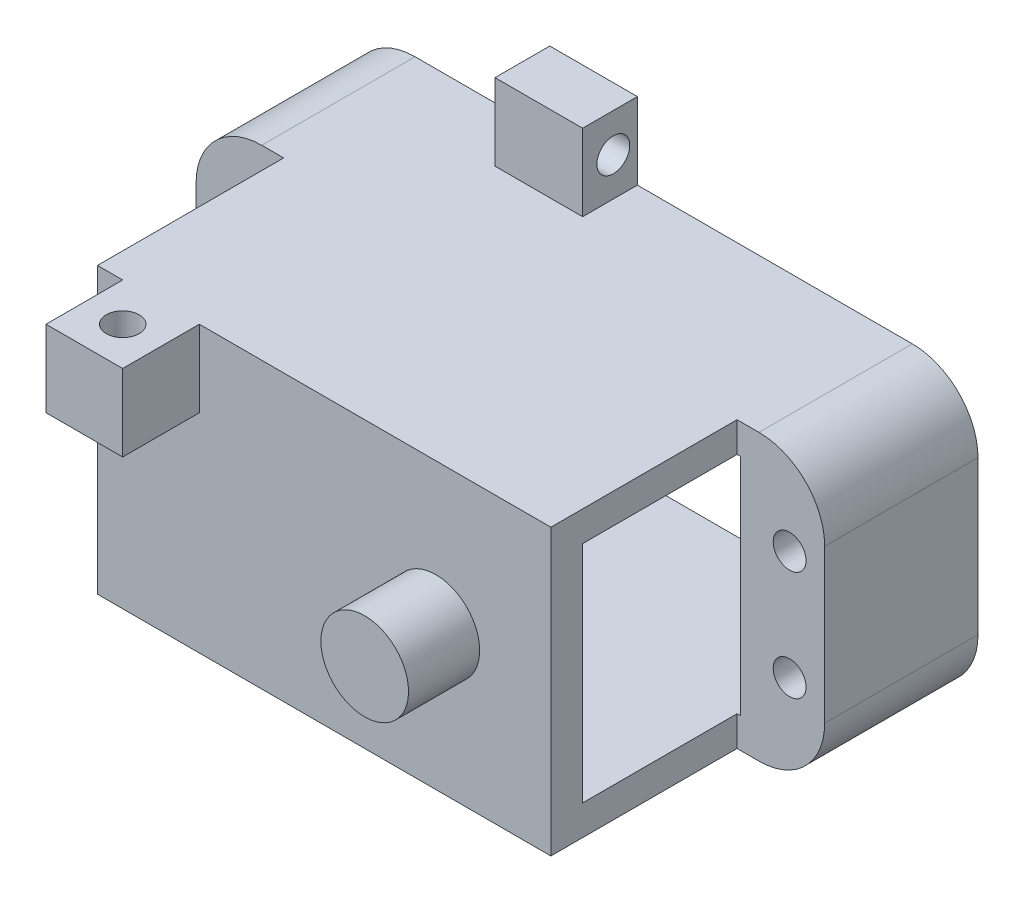
SolidWorks part; units mm, degrees
ref_plane "Спереди" through (0, 0, 0) normal (0, 0, 1) x (1, 0, 0)
ref_plane "Сверху" through (0, 0, 0) normal (0, 1, 0) x (1, 0, 0)
ref_plane "Справа" through (0, 0, 0) normal (1, 0, 0) x (0, 0, -1)
sketch "Эскиз1" plane through (0, 0, 0) normal (0, 0, 1) x (1, 0, 0)
  line L1 (-28.7, -13) -> (28.7, -13)
  line L2 (-28.7, -13) -> (-28.7, 13)
  line L3 (-28.7, 13) -> (28.7, 13)
  line L4 (28.7, -13) -> (28.7, 13)
  line L5 (-28.7, -13) -> (28.7, 13) construction
  line L6 (-28.7, 13) -> (28.7, -13) construction
  point P0 (0, 0)
  dimension "D1" = 26
  dimension "D2" = 57.4
extrude "Бобышка-Вытянуть1" add sketch "Эскиз1" along normal blind 31
sketch "Эскиз3" plane through (0, 0, 0) normal (0, 0, 1) x (1, 0, 0)
  line L1 (-21, -10.25) -> (21, -10.25)
  line L2 (-21, -10.25) -> (-21, 10.25)
  line L3 (-21, 10.25) -> (21, 10.25)
  line L4 (21, -10.25) -> (21, 10.25)
  line L5 (-21, -10.25) -> (21, 10.25) construction
  line L6 (-21, 10.25) -> (21, -10.25) construction
  point P0 (0, 0)
  dimension "D1" = 42
  dimension "D2" = 20.5
extrude "Вырез-Вытянуть1" cut sketch "Эскиз3" along normal blind 28.1
sketch "Эскиз5" plane through (0, 0, 0) normal (0, 0, 1) x (1, 0, 0)
  line L0 (-28.7, 13) -> (-18.4, 13)
  line L1 (28.7, 13) -> (-28.7, 13) construction
  line L3 (-18.4, 13) -> (-11.4, 13)
  line L4 (-18.4, 13) -> (-18.4, 6)
  line L5 (-18.4, 6) -> (-11.4, 6)
  line L6 (-11.4, 13) -> (-11.4, 6)
  dimension "D1" = 10.3
  dimension "D2" = 7
  dimension "D3" = 7
extrude "Бобышка-Вытянуть2" add sketch "Эскиз5" along normal blind 7 from surface at 31 contours L3 L6 L5 L4 starting at face at (0, 0, 31)
sketch "Эскиз6" plane through (0, 0, 0) normal (0, 0, 1) x (1, 0, 0)
  line L0 (-28.7, 13) -> (-10.4, 13)
  line L1 (28.7, 13) -> (-11.4, 13) construction
  line L3 (-10.4, 13) -> (-2.4, 13)
  line L4 (-10.4, 13) -> (-10.4, 20)
  line L5 (-10.4, 20) -> (-2.4, 20)
  line L6 (-2.4, 13) -> (-2.4, 20)
  dimension "D1" = 18.3
  dimension "D2" = 8
  dimension "D3" = 7
extrude "Бобышка-Вытянуть3" add sketch "Эскиз6" along normal blind 5 contours L3 L6 L5 L4
sketch "Эскиз7" plane through (0, 13, 0) normal (0, 1, 0) x (1, 0, 0)
  line L0 (-18.4, -31) -> (-14.9, -31)
  line L1 (-14.9, -31) -> (-14.9, -34.5)
  circle A0 centre (-14.9, -34.5) radius 1.5
  dimension "D3" = 3
  dimension "D1" = 3.5
  dimension "D2" = 3.5
extrude "Вырез-Вытянуть2" cut sketch "Эскиз7" against normal up to surface (7 mm away) contours A0 up to face at (-14.9, 6, 34.5)
sketch "Эскиз8" plane through (-10.4, 0, 0) normal (-1, 0, 0) x (0, 0, 1)
  line L0 (0, 20) -> (0, 16.5)
  line L1 (0, 13) -> (0, 20) construction
  line L2 (0, 16.5) -> (2.2, 16.5)
  circle A0 centre (2.2, 16.5) radius 1.5
  dimension "D2" = 3
  dimension "D1" = 2.2
extrude "Вырез-Вытянуть3" cut sketch "Эскиз8" against normal up to surface (8 mm away) contours A0 up to face at (-2.4, 16.5, 2.5)
sketch "Эскиз10" plane through (-28.7, 0, 0) normal (-1, 0, 0) x (0, 0, 1)
  line L0 (0, 0) -> (14, 0)
  line L1 (0, 13) -> (0, -13) construction
  line L2 (14, 0) -> (14, 13)
  line L3 (31, 13) -> (0, 13) construction
  line L5 (14, 13) -> (31, 13)
  line L6 (14, 13) -> (14, -13)
  line L7 (14, -13) -> (31, -13)
  line L8 (31, 13) -> (31, -13)
  line M3 (0, -13) -> (31, -13)
  line M4 (31, -13) -> (31, 13)
  line M5 (31, 13) -> (0, 13)
  dimension "D1" = 14
extrude "Вырез-Вытянуть4" cut sketch "Эскиз10" against normal blind 8 contours L2 L6 M3 M4 M5
ref_plane "Плоскость4" through (0, 0, 0) normal (1, 0, 0) x (0, 0, -1)
mirror "Зеркальное отражение1" about plane through (0, 0, 0) normal (1, 0, 0) of "Вырез-Вытянуть4"
sketch "Эскиз14" plane through (0, 0, 0) normal (0, 0, -1) x (-1, 0, 0)
  line L0 (-28.7, 0) -> (-25.5, 0)
  line L1 (-28.7, -13) -> (-28.7, 13) construction
  line L2 (-25.5, -5) -> (-25.5, 5)
  circle A0 centre (-25.5, 5) radius 1.5
  circle A1 centre (-25.5, -5) radius 1.5
  point P8 (-25.5, 0)
  dimension "D1" = 3.2
  dimension "D3" = 3
  dimension "D2" = 10
extrude "Вырез-Вытянуть7" cut sketch "Эскиз14" against normal up to surface (14 mm away) contours A0 | A1
mirror "Зеркальное отражение3" about plane through (0, 0, 0) normal (1, 0, 0) of "Вырез-Вытянуть7"
fillet "Скругление1" radius 6 4 edges at (-28.7, 13, 7) (-28.7, -13, 7) (28.7, -13, 7) (28.7, 13, 7)
sketch "Эскиз15" plane through (0, 0, 31) normal (0, 0, 1) x (1, 0, 0)
  circle A0 centre (10.2, 0) radius 4
  circle A1 centre (10.2, 0) radius 11.05 construction
  dimension "D1" = 8
extrude "Бобышка-Вытянуть4" add sketch "Эскиз15" along normal blind 6.5
